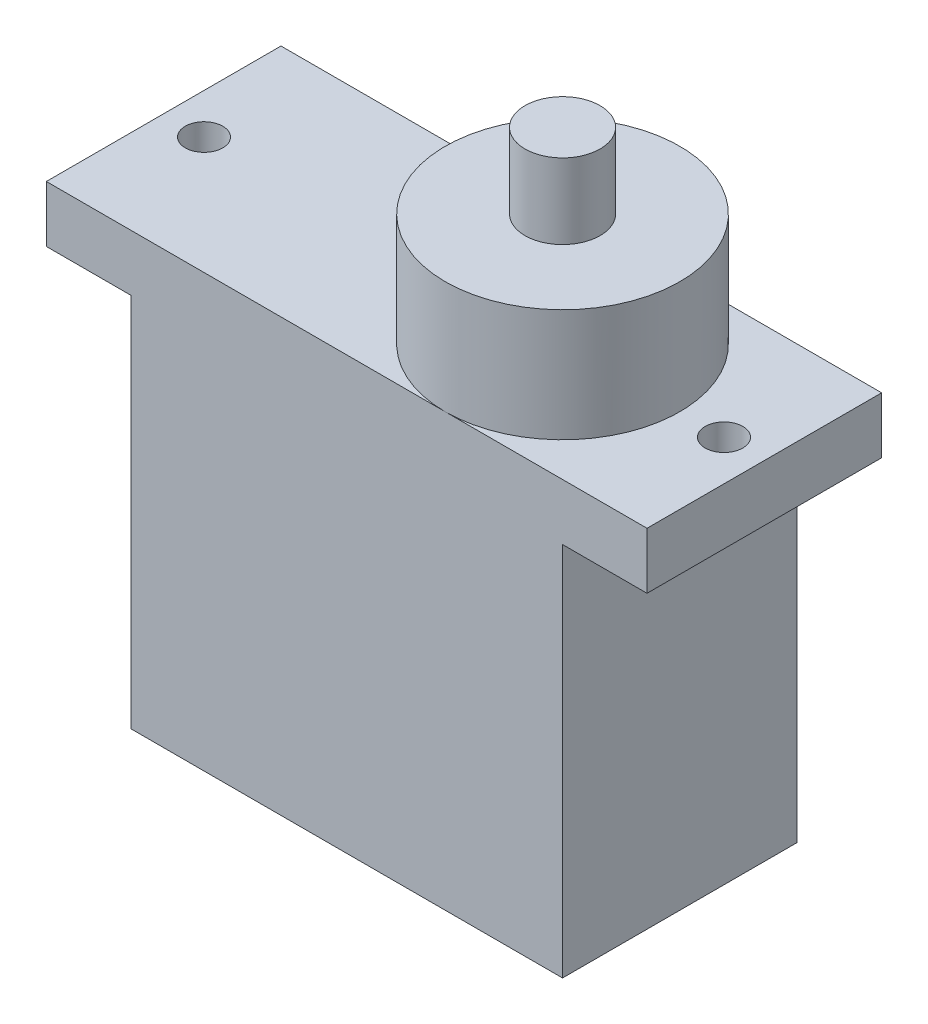
SolidWorks part; units mm, degrees
material "ABS"
ref_plane "前视基准面" through (0, 0, 0) normal (0, 0, 1) x (1, 0, 0)
ref_plane "上视基准面" through (0, 0, 0) normal (0, 1, 0) x (1, 0, 0)
ref_plane "右视基准面" through (0, 0, 0) normal (1, 0, 0) x (0, 0, -1)
sketch "草图1" plane through (0, 0, 0) normal (0, 1, 0) x (1, 0, 0)
  line L1 (-11.5, 6.25) -> (11.5, 6.25)
  line L2 (-11.5, 6.25) -> (-11.5, -6.25)
  line L3 (-11.5, -6.25) -> (11.5, -6.25)
  line L4 (11.5, 6.25) -> (11.5, -6.25)
  line L5 (-11.5, 6.25) -> (11.5, -6.25) construction
  line L6 (-11.5, -6.25) -> (11.5, 6.25) construction
  point P0 (0, 0)
  dimension "D1" = 23
  dimension "D2" = 12.5
extrude "凸台-拉伸1" add sketch "草图1" along normal blind 20
ref_plane "基准面1" through (0, 20, 0) normal (0, 1, 0) x (1, 0, 0)
sketch "草图2" plane through (0, 20, 0) normal (0, 1, 0) x (1, 0, 0)
  line L0 (0, 0) -> (13.85, 0) construction
  line L1 (-16, 6.25) -> (16, 6.25)
  line L2 (-16, 6.25) -> (-16, -6.25)
  line L3 (-16, -6.25) -> (16, -6.25)
  line L4 (16, 6.25) -> (16, -6.25)
  line L5 (-16, 6.25) -> (16, -6.25) construction
  line L6 (-16, -6.25) -> (16, 6.25) construction
  line L7 (0, 6.25) -> (0, -6.25) construction
  circle A0 centre (13.85, 0) radius 1
  circle A1 centre (-13.85, 0) radius 1
  point P0 (0, 0)
  dimension "D3" = 2
  dimension "D1" = 32
  dimension "D2" = 13.85
extrude "凸台-拉伸2" add sketch "草图2" along normal blind 3
ref_plane "基准面2" through (0, 23, 0) normal (0, 1, 0) x (1, 0, 0)
sketch "草图4" plane through (0, 23, 0) normal (0, 1, 0) x (1, 0, 0)
  line L0 (11.5, -6.25) -> (11.5, 6.25) construction
  line L1 (-16, -6.25) -> (16, -6.25) construction
  line L2 (16, 6.25) -> (-16, 6.25) construction
  circle A0 centre (5.25, 0) radius 6.25
extrude "凸台-拉伸3" add sketch "草图4" along normal blind 6
ref_plane "基准面3" through (0, 29, 0) normal (0, 1, 0) x (1, 0, 0)
sketch "草图5" plane through (0, 29, 0) normal (0, 1, 0) x (1, 0, 0)
  circle A0 centre (5.25, 0) radius 2
  dimension "D1" = 4
extrude "凸台-拉伸4" add sketch "草图5" along normal blind 4
